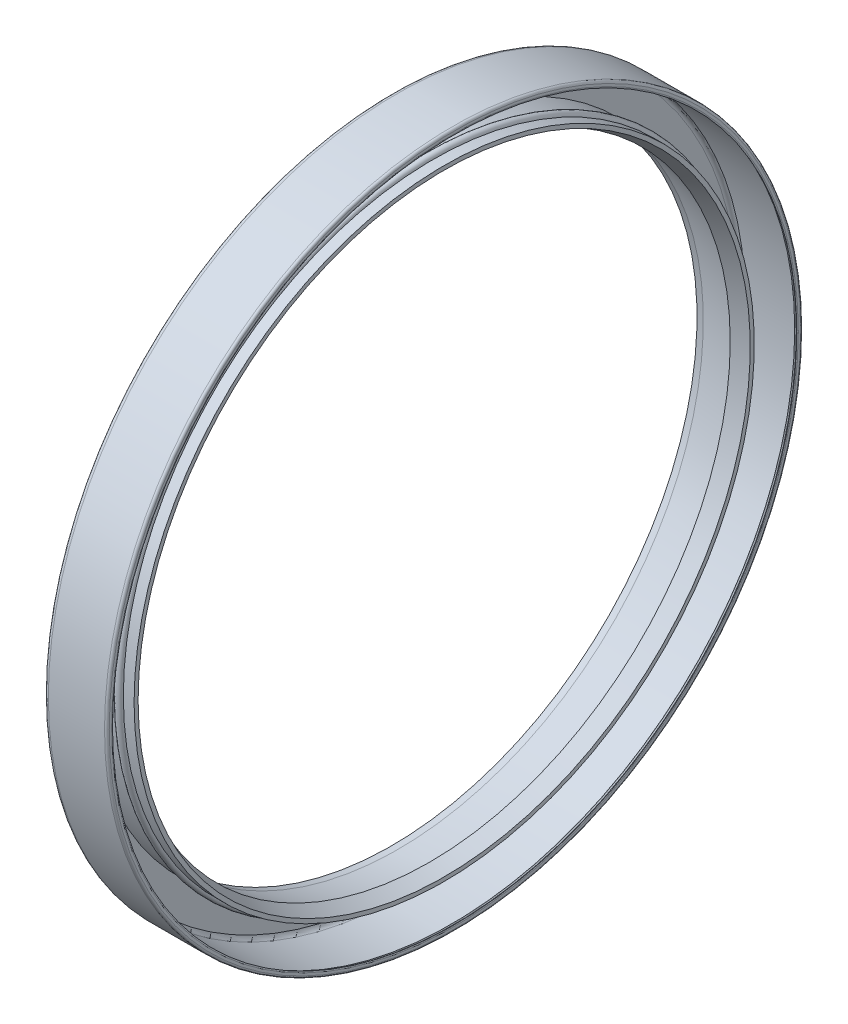
SolidWorks part; units mm, degrees
ref_plane "Piano frontale" through (0, 0, 0) normal (0, 0, 1) x (1, 0, 0)
ref_plane "Piano superiore" through (0, 0, 0) normal (0, 1, 0) x (1, 0, 0)
ref_plane "Piano destro" through (0, 0, 0) normal (1, 0, 0) x (0, 0, -1)
ref_plane "Piano1" through (0, 0, 0) normal (0, 0, 1) x (1, 0, 0)
sketch "Schizzo1" plane through (0, 0, 0) normal (0, 0, 1) x (1, 0, 0)
  line L0 (0, 54.25) -> (0, 48.25)
  line L1 (0, 48.25) -> (1, 48.25)
  line L2 (1, 48.25) -> (6, 47.5)
  line L3 (6, 47.5) -> (8.3, 48.3625)
  line L4 (8.3, 48.3625) -> (8.3, 49)
  line L5 (8.3, 49) -> (6.6, 49)
  line L6 (5.4, 49) -> (1, 49)
  line L7 (1, 49) -> (1, 53.65)
  line L8 (1.6, 54.25) -> (9.4375, 54.25)
  line L9 (9.7874, 54.1562) -> (9.9498, 54.0625)
  line L10 (10, 54.25) -> (10, 54.625)
  line L11 (9.625, 55) -> (0.75, 55)
  line L12 (50, 0) -> (-50, 0) construction
  arc A0 (6.6, 49) -> (5.4, 49) centre (6, 49) ccw
  arc A1 (1, 53.65) -> (1.6, 54.25) centre (1.6, 53.65) cw
  arc A2 (9.4375, 54.25) -> (9.7874, 54.1562) centre (9.625, 54.25) cw
  arc A3 (9.9498, 54.0625) -> (10, 54.25) centre (9.625, 54.25) ccw
  arc A4 (10, 54.625) -> (9.625, 55) centre (9.625, 54.625) ccw
  arc A5 (0.75, 55) -> (0, 54.25) centre (0.75, 54.25) ccw
revolve "Rivoluzione1" add sketch "Schizzo1" angle 360 about L12
